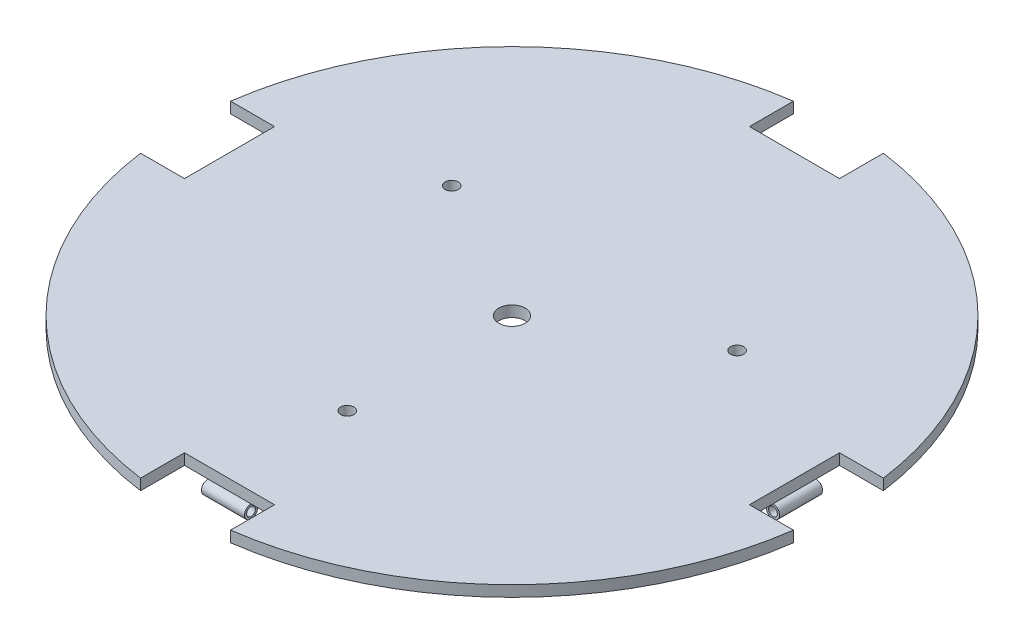
SolidWorks part; units mm, degrees
ref_plane "Front Plane" through (0, 0, 0) normal (0, 0, 1) x (1, 0, 0)
ref_plane "Top Plane" through (0, 0, 0) normal (0, 1, 0) x (1, 0, 0)
ref_plane "Right Plane" through (0, 0, 0) normal (1, 0, 0) x (0, 0, -1)
sketch "Sketch1" plane through (0, 0, 0) normal (0, 1, 0) x (1, 0, 0)
  circle A0 centre (0, 0) radius 150
  dimension "D1" = 300
extrude "Boss-Extrude1" add sketch "Sketch1" along normal blind 5
sketch "Sketch2" plane through (0, 5, 0) normal (0, 1, 0) x (1, 0, 0)
  circle A0 centre (0, 0) radius 6
  dimension "D1" = 12
extrude "Cut-Extrude1" cut sketch "Sketch2" against normal through all both and the other way through all
sketch "Sketch3" plane through (0, 5, 0) normal (0, 1, 0) x (1, 0, 0)
  line L0 (64.9519, 37.5) -> (-64.9519, 37.5) construction
  line L1 (-64.9519, 37.5) -> (0, -75) construction
  line L2 (0, -75) -> (64.9519, 37.5) construction
  circle A0 centre (0, 0) radius 75 construction
  circle A1 centre (-64.9519, 37.5) radius 3
  circle A2 centre (64.9519, 37.5) radius 3
  circle A3 centre (0, -75) radius 3
  dimension "D1" = 150
  dimension "D2" = 6
extrude "Cut-Extrude2" cut sketch "Sketch3" against normal through all both and the other way through all
sketch "Sketch4" plane through (0, 5, 0) normal (0, 1, 0) x (1, 0, 0)
  line L0 (-20.5, -148.5926) -> (-20.5, -128.5926)
  line L1 (-20.5, -128.5926) -> (20.5, -128.5926)
  line L2 (20.5, -128.5926) -> (20.5, -148.5926)
  line L3 (-20.5, 148.5926) -> (-20.5, 128.5926)
  line L4 (-20.5, 128.5926) -> (20.5, 128.5926)
  line L5 (20.5, 128.5926) -> (20.5, 148.5926)
  line L6 (-148.5926, 20.5) -> (-128.5926, 20.5)
  line L7 (-128.5926, 20.5) -> (-128.5926, -20.5)
  line L8 (-128.5926, -20.5) -> (-148.5926, -20.5)
  line L9 (148.5926, 20.5) -> (128.5926, 20.5)
  line L10 (128.5926, 20.5) -> (128.5926, -20.5)
  line L11 (128.5926, -20.5) -> (148.5926, -20.5)
  circle A0 centre (0, 0) radius 150
  circle A1 centre (0, 0) radius 150 construction
  circle M11 centre (0, 0) radius 150
  dimension "D1" = 41
  dimension "D2" = 20
extrude "Cut-Extrude3" cut sketch "Sketch4" against normal through all both and the other way through all contours L4 L5 L3 M11 | L8 L7 L6 M11 | L10 L11 L9 M11 | L2 L1 L0 M11
sketch "Sketch5" plane through (0, 0, 0) normal (0, 0, 1) x (1, 0, 0)
  line L0 (-128.5926, 0) -> (-125.5926, 0)
  line L1 (-125.5926, 0) -> (-125.5926, -3)
  line L2 (-148.5926, 0) -> (-20.5, 0) construction
  circle A0 centre (-128.5926, -3) radius 3
  circle A1 centre (-128.5926, -3) radius 2
  point P5 (0, 0)
  point P7 (-127.8232, 0.7844)
  point P8 (-127.7398, 0)
  point P11 (-127.39, 0)
  point P13 (0, 0)
  point P14 (0, 0)
  point P15 (-127.9258, 0)
  point P16 (0, 0)
  dimension "D1" = 1
  dimension "D2" = 4
extrude "Boss-Extrude2" add sketch "Sketch5" along normal blind 9.8 and the other way blind 9.8 contours A0 L1 L0 | A0 A1
pattern_circular "CirPattern1" count 4 over 360 about axis through (0, 0, 0) along (0, 1, 0) of "Boss-Extrude2"
